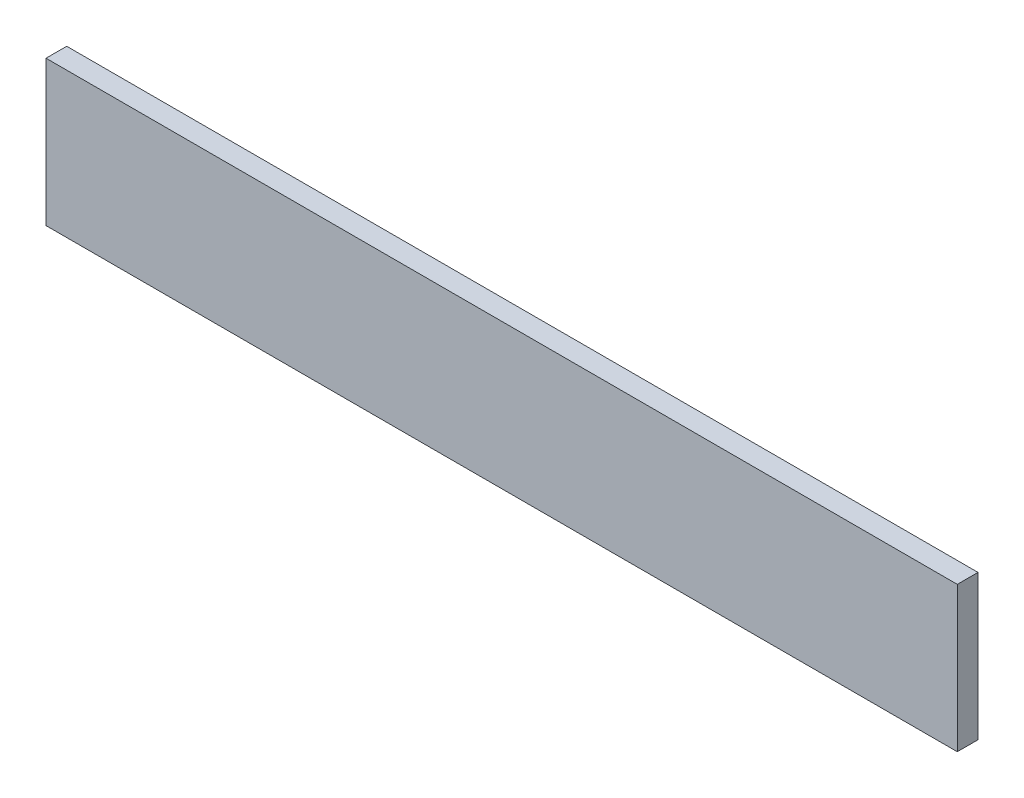
SolidWorks part; units mm, degrees
ref_plane "Front Plane" through (0, 0, 0) normal (0, 0, 1) x (1, 0, 0)
ref_plane "Top Plane" through (0, 0, 0) normal (0, 1, 0) x (1, 0, 0)
ref_plane "Right Plane" through (0, 0, 0) normal (1, 0, 0) x (0, 0, -1)
sketch "Sketch1" plane through (0, 0, 0) normal (0, 0, 1) x (1, 0, 0)
  line L1 (0, 0) -> (110, 0)
  line L2 (0, 0) -> (0, 17.5)
  line L3 (0, 17.5) -> (110, 17.5)
  line L4 (110, 0) -> (110, 17.5)
  dimension "D1" = 110
  dimension "D2" = 17.5
extrude "Boss-Extrude1" add sketch "Sketch1" along normal blind 2.5
